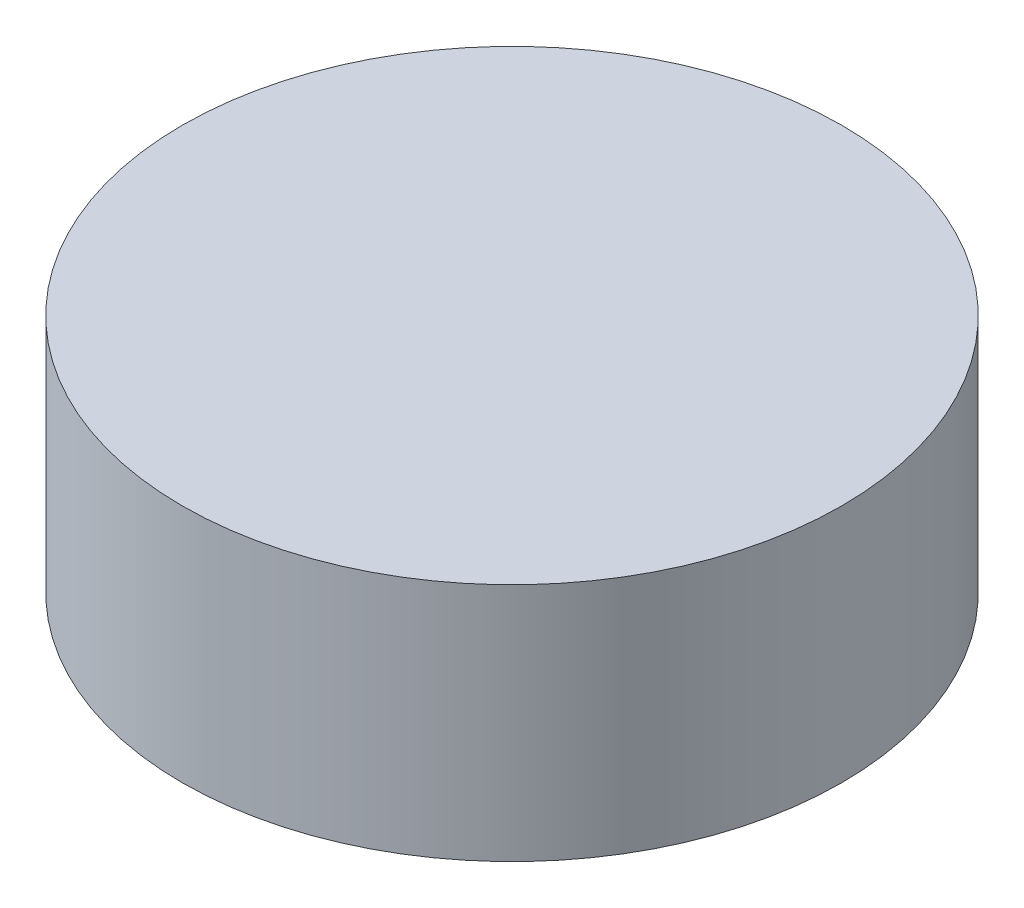
SolidWorks part; units mm, degrees
ref_plane "Front Plane" through (0, 0, 0) normal (0, 0, 1) x (1, 0, 0)
ref_plane "Top Plane" through (0, 0, 0) normal (0, 1, 0) x (1, 0, 0)
ref_plane "Right Plane" through (0, 0, 0) normal (1, 0, 0) x (0, 0, -1)
sketch "Sketch1" plane through (0, 0, 0) normal (0, 1, 0) x (1, 0, 0)
  circle A0 centre (0, 0) radius 5.5
  dimension "D1" = 11
extrude "Boss-Extrude1" add sketch "Sketch1" along normal blind 4
